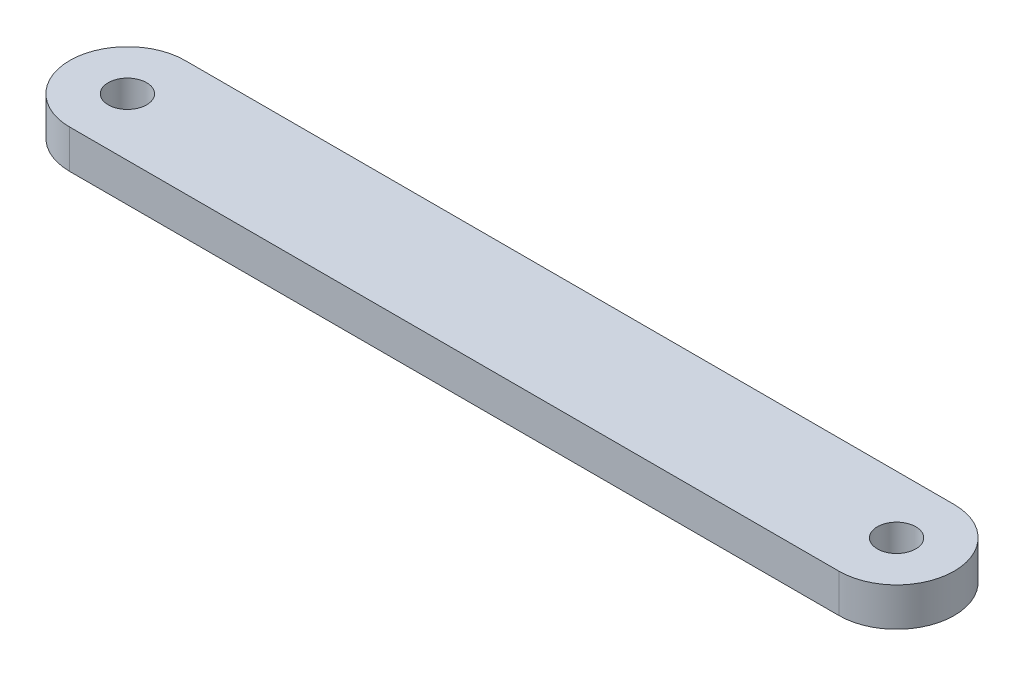
SolidWorks part; units mm, degrees
ref_plane "Front Plane" through (0, 0, 0) normal (0, 0, 1) x (1, 0, 0)
ref_plane "Top Plane" through (0, 0, 0) normal (0, 1, 0) x (1, 0, 0)
ref_plane "Right Plane" through (0, 0, 0) normal (1, 0, 0) x (0, 0, -1)
sketch "Sketch1" plane through (0, 0, 0) normal (0, 1, 0) x (1, 0, 0)
  line L1 (-50, 7.5) -> (50, 7.5)
  line L3 (-50, -7.5) -> (50, -7.5)
  line L5 (-50, 7.5) -> (50, -7.5) construction
  line L6 (-50, -7.5) -> (50, 7.5) construction
  arc A0 (-50, 7.5) -> (-50, -7.5) centre (-50, 0) ccw
  arc A1 (50, 7.5) -> (50, -7.5) centre (50, 0) cw
  circle A2 centre (-50, 0) radius 2.5
  circle A3 centre (50, 0) radius 2.5
  point P0 (0, 0)
  dimension "D3" = 5
  dimension "D4" = 5
  dimension "D1" = 100
  dimension "D2" = 15
extrude "Boss-Extrude1" add sketch "Sketch1" along normal blind 5
